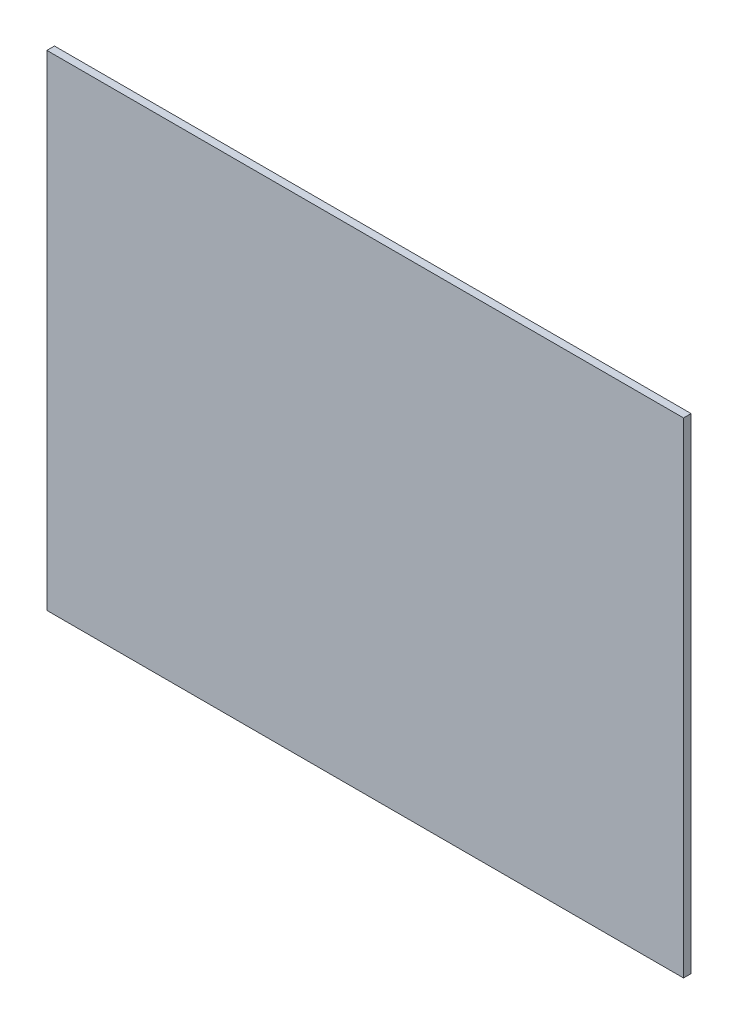
SolidWorks part; units mm, degrees
ref_plane "Plan de face" through (0, 0, 0) normal (0, 0, 1) x (1, 0, 0)
ref_plane "Plan de dessus" through (0, 0, 0) normal (0, 1, 0) x (1, 0, 0)
ref_plane "Plan de droite" through (0, 0, 0) normal (1, 0, 0) x (0, 0, -1)
sketch "Esquisse2" plane through (0, 0, 0) normal (0, 0, 1) x (1, 0, 0)
  line L1 (-210, -160) -> (210, -160)
  line L2 (-210, -160) -> (-210, 160)
  line L3 (-210, 160) -> (210, 160)
  line L4 (210, -160) -> (210, 160)
  line L5 (-210, -160) -> (210, 160) construction
  line L6 (-210, 160) -> (210, -160) construction
  point P0 (0, 0)
  dimension "D1" = 320
  dimension "D2" = 420
extrude "Boss.-Extru.1" add sketch "Esquisse2" along normal blind 5
